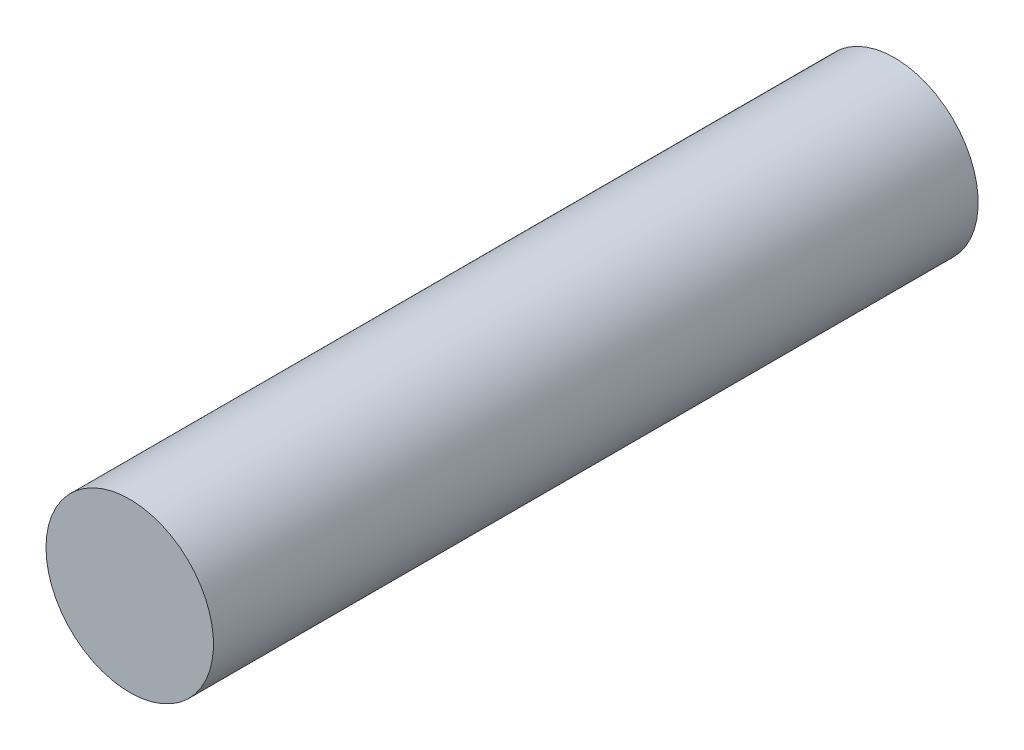
SolidWorks part; units mm, degrees
ref_plane "정면" through (0, 0, 0) normal (0, 0, 1) x (1, 0, 0)
ref_plane "윗면" through (0, 0, 0) normal (0, 1, 0) x (1, 0, 0)
ref_plane "우측면" through (0, 0, 0) normal (1, 0, 0) x (0, 0, -1)
sketch "스케치1" plane through (0, 0, 0) normal (0, 0, 1) x (1, 0, 0)
  circle A0 centre (0, 0) radius 1.5
  dimension "D1" = 3
extrude "보스-돌출1" add sketch "스케치1" along normal blind 13.7
